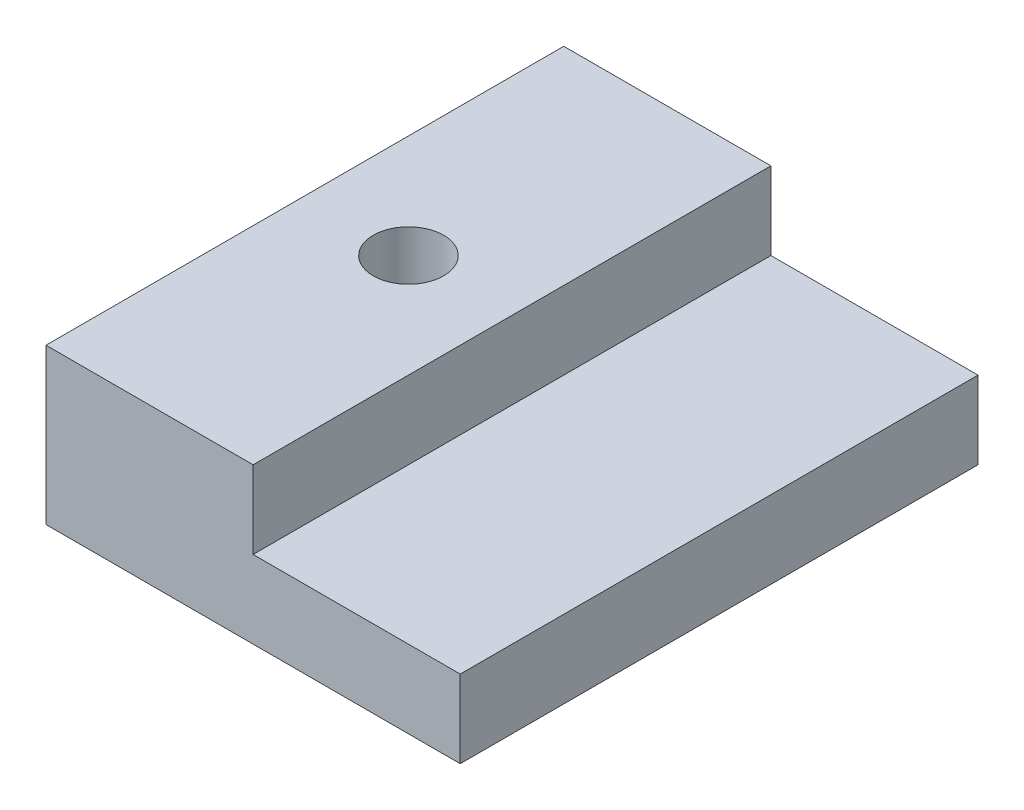
SolidWorks part; units mm, degrees
material "6061-T6 (SS)"
ref_plane "Front Plane" through (0, 0, 0) normal (0, 0, 1) x (1, 0, 0)
ref_plane "Top Plane" through (0, 0, 0) normal (0, 1, 0) x (1, 0, 0)
ref_plane "Right Plane" through (0, 0, 0) normal (1, 0, 0) x (0, 0, -1)
sketch "Sketch1" plane through (0, 0, 0) normal (0, 1, 0) x (1, 0, 0)
  line L1 (0, 0) -> (20, 0)
  line L2 (0, 0) -> (0, 50)
  line L3 (0, 50) -> (20, 50)
  line L4 (20, 0) -> (20, 50)
  dimension "D1" = 20
  dimension "D2" = 50
extrude "Boss-Extrude1" add sketch "Sketch1" along normal blind 15
sketch "Sketch3" plane through (0, 0, 0) normal (0, -1, 0) x (-1, 0, 0)
  line L0 (-20, 50) -> (0, 50) construction
  line L1 (-20, 0) -> (-40, 0)
  line L2 (-20, 0) -> (-20, 50)
  line L3 (-20, 50) -> (-40, 50)
  line L4 (-40, 0) -> (-40, 50)
  dimension "D1" = 20
extrude "Boss-Extrude2" add sketch "Sketch3" against normal blind 7.5
hole_wizard "M8x1.25 Tapped Hole1" positions "Sketch4" profile "Sketch5" tap size "M8x1.25" standard "ANSI Metric" end condition up to next
sketch "Sketch4" plane through (0, 15, 0) normal (0, 1, 0) x (1, 0, 0)
  line L3 (10, 50) -> (10, 0) construction
  line L4 (20, 50) -> (0, 50) construction
  line L5 (0, 0) -> (20, 0) construction
  point P0 (10, 25)
  point P15 (10, 25)
sketch "Sketch5" plane through (10, 15, -25) normal (1, 0, 0) x (0, 0, 1)
  line L0 (0, 0) -> (0, 15)
  line L1 (0, 15) -> (3.4, 15)
  line L2 (3.4, 15) -> (3.4, 0)
  line L5 (3.4, 0) -> (0, 0)
  line L11 (0, -6.35) -> (0, 107.95) construction
  dimension "Thru Tap Drill Dia." = 6.8
  dimension "Thru Tap Drill Depth" = 15
cosmetic thread "Hole Thread1" parameters "D2"=8
